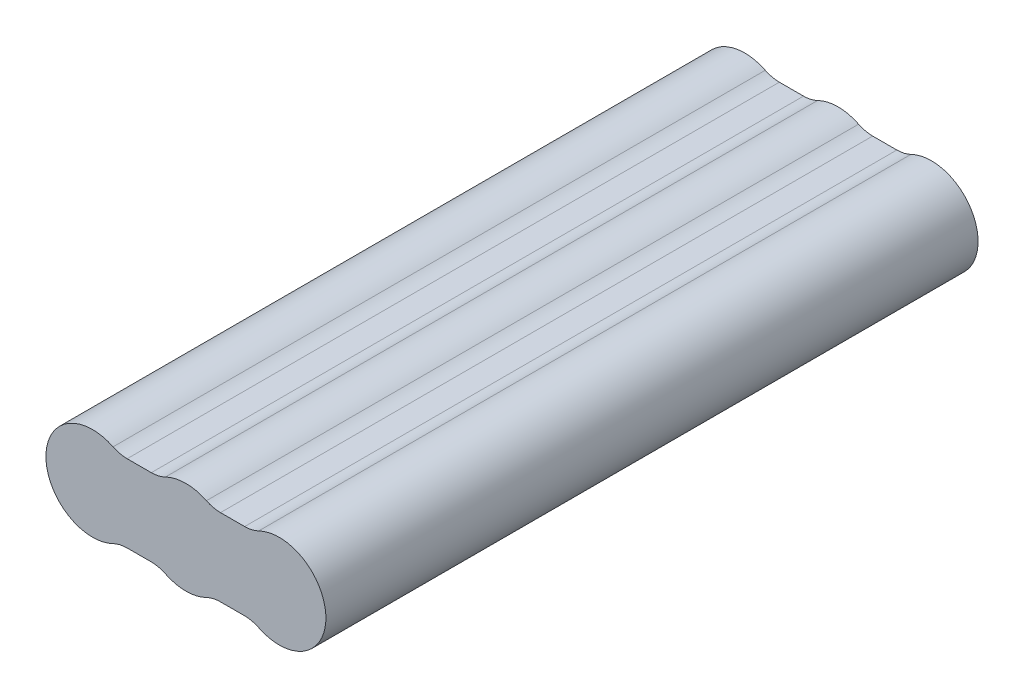
SolidWorks part; units mm, degrees
ref_plane "Front Plane" through (0, 0, 0) normal (0, 0, 1) x (1, 0, 0)
ref_plane "Top Plane" through (0, 0, 0) normal (0, 1, 0) x (1, 0, 0)
ref_plane "Right Plane" through (0, 0, 0) normal (1, 0, 0) x (0, 0, -1)
sketch "Sketch1" plane through (0, 0, 0) normal (0, 0, 1) x (1, 0, 0)
  line L0 (3220.7504, 2866.9751) -> (3225.5407, 2866.9751)
  line L1 (3220.7504, 2851.6462) -> (3225.5407, 2851.6462)
  line L2 (3239.2543, 2866.9751) -> (3244.0446, 2866.9751)
  line L3 (3239.2543, 2851.6462) -> (3244.0446, 2851.6462)
  arc A0 (3246.8353, 2851.0001) -> (3246.8353, 2867.6212) centre (3250.9014, 2859.3107) ccw
  arc A1 (3228.3314, 2851.0001) -> (3236.4636, 2851.0001) centre (3232.3975, 2859.3107) ccw
  arc A2 (3236.4636, 2867.6212) -> (3228.3314, 2867.6212) centre (3232.3975, 2859.3107) ccw
  arc A3 (3217.9597, 2867.6212) -> (3217.9597, 2851.0001) centre (3213.8936, 2859.3107) ccw
  arc A4 (3217.9597, 2867.6212) -> (3220.7504, 2866.9751) centre (3220.7504, 2873.3251) ccw
  arc A5 (3225.5407, 2866.9751) -> (3228.3314, 2867.6212) centre (3225.5407, 2873.3251) ccw
  arc A6 (3220.7504, 2851.6462) -> (3217.9597, 2851.0001) centre (3220.7504, 2845.2962) ccw
  arc A7 (3228.3314, 2851.0001) -> (3225.5407, 2851.6462) centre (3225.5407, 2845.2962) ccw
  arc A8 (3236.4636, 2867.6212) -> (3239.2543, 2866.9751) centre (3239.2543, 2873.3251) ccw
  arc A9 (3244.0446, 2866.9751) -> (3246.8353, 2867.6212) centre (3244.0446, 2873.3251) ccw
  arc A10 (3239.2543, 2851.6462) -> (3236.4636, 2851.0001) centre (3239.2543, 2845.2962) ccw
  arc A11 (3246.8353, 2851.0001) -> (3244.0446, 2851.6462) centre (3244.0446, 2845.2962) ccw
extrude "Boss-Extrude1" add sketch "Sketch1" along normal blind 129.3114
